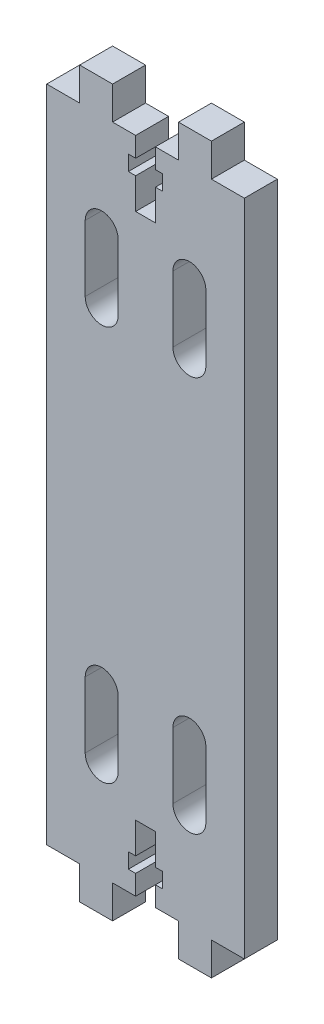
SolidWorks part; units mm, degrees
ref_plane "Front Plane" through (0, 0, 0) normal (0, 0, 1) x (1, 0, 0)
ref_plane "Top Plane" through (0, 0, 0) normal (0, 1, 0) x (1, 0, 0)
ref_plane "Right Plane" through (0, 0, 0) normal (1, 0, 0) x (0, 0, -1)
sketch "Sketch1" plane through (0, 0, 0) normal (0, 0, 1) x (1, 0, 0)
  line L0 (0, 72.0719) -> (0, -22.2682) construction
  line L1 (-15, 50) -> (-15, -50)
  line L2 (15, 50) -> (15, -50)
  line L3 (0, 0) -> (45.6439, 0) construction
  line L4 (-15, 50) -> (15, 50)
  line L5 (-15, -50) -> (15, -50)
  line L6 (-6.6565, -35) -> (-6.6565, -25) construction
  line L7 (-9.1565, -35) -> (-9.1565, -25)
  line L8 (-4.1565, -35) -> (-4.1565, -25)
  line L9 (6.6565, -35) -> (6.6565, -25) construction
  line L10 (9.1565, -35) -> (9.1565, -25)
  line L11 (4.1565, -35) -> (4.1565, -25)
  line L12 (6.6565, 35) -> (6.6565, 25) construction
  line L13 (9.1565, 35) -> (9.1565, 25)
  line L14 (4.1565, 35) -> (4.1565, 25)
  line L15 (-6.6565, 35) -> (-6.6565, 25) construction
  line L16 (-9.1565, 35) -> (-9.1565, 25)
  line L17 (-4.1565, 35) -> (-4.1565, 25)
  arc A0 (-9.1565, -35) -> (-4.1565, -35) centre (-6.6565, -35) ccw
  arc A1 (-4.1565, -25) -> (-9.1565, -25) centre (-6.6565, -25) ccw
  arc A2 (9.1565, -35) -> (4.1565, -35) centre (6.6565, -35) cw
  arc A3 (4.1565, -25) -> (9.1565, -25) centre (6.6565, -25) cw
  arc A4 (9.1565, 35) -> (4.1565, 35) centre (6.6565, 35) ccw
  arc A5 (4.1565, 25) -> (9.1565, 25) centre (6.6565, 25) ccw
  arc A6 (-9.1565, 35) -> (-4.1565, 35) centre (-6.6565, 35) cw
  arc A7 (-4.1565, 25) -> (-9.1565, 25) centre (-6.6565, 25) cw
  point P11 (-6.6565, -30)
  point P16 (0, 0)
  point P17 (0, 0)
  point P18 (0, 0)
  point P19 (0, 0)
  point P22 (6.6565, -30)
  point P29 (6.6565, 30)
  point P36 (-6.6565, 30)
  line B0 (-2.6, -47) -> (-2.6, -44.7)
  line B1 (1.5, -44.7) -> (1.5, -40)
  line B2 (-1.5, -40) -> (-1.5, -44.7)
  line B3 (-2.6, -44.7) -> (-1.5, -44.7)
  line B4 (0, -50) -> (0, -38.7792) construction
  line B5 (-1.5, -50) -> (-5, -50)
  line B6 (-5, -55) -> (-10, -55)
  line B7 (-10, -55) -> (-10, -50)
  line B8 (-5, -55) -> (-5, -50)
  line B9 (1.5, -50) -> (5, -50)
  line B10 (5, -50) -> (5, -55)
  line B11 (5, -55) -> (10, -55)
  line B12 (10, -55) -> (10, -50)
  line B13 (1.5, -50) -> (1.5, -47)
  line B14 (0, -40) -> (0, -50) construction
  line B15 (-1.5, -47) -> (-1.5, -50)
  line B16 (2.6, -44.7) -> (2.6, -47)
  line B17 (-1.5, -50) -> (1.5, -50) construction
  line B18 (1.5, -44.7) -> (2.6, -44.7)
  line B19 (2.6, -47) -> (1.5, -47)
  line B20 (1.5, -40) -> (-1.5, -40)
  line B21 (-1.5, -47) -> (-2.6, -47)
  line B22 (2.6, 47) -> (2.6, 44.7)
  line B23 (-1.5, 44.7) -> (-1.5, 40)
  line B24 (1.5, 40) -> (1.5, 44.7)
  line B25 (2.6, 44.7) -> (1.5, 44.7)
  line B26 (0, 50) -> (0, 38.7792) construction
  line B27 (1.5, 50) -> (5, 50)
  line B28 (5, 55) -> (10, 55)
  line B29 (10, 55) -> (10, 50)
  line B30 (5, 55) -> (5, 50)
  line B31 (-1.5, 50) -> (-5, 50)
  line B32 (-5, 50) -> (-5, 55)
  line B33 (-5, 55) -> (-10, 55)
  line B34 (-10, 55) -> (-10, 50)
  line B35 (-1.5, 50) -> (-1.5, 47)
  line B36 (0, 40) -> (0, 50) construction
  line B37 (1.5, 47) -> (1.5, 50)
  line B38 (-2.6, 44.7) -> (-2.6, 47)
  line B39 (1.5, 50) -> (-1.5, 50) construction
  line B40 (-1.5, 44.7) -> (-2.6, 44.7)
  line B41 (-2.6, 47) -> (-1.5, 47)
  line B42 (-1.5, 40) -> (1.5, 40)
  line B43 (1.5, 47) -> (2.6, 47)
sketch_block_instance "Insert M3 plots ep 5mm-1"
sketch_block "Insert M3 plots ep 5mm"
sketch_block_instance "Decoupe Insert M3-4"
sketch_block "Decoupe Insert M3" parameters "D1"=5.2, "D2"=3, "D3"=2.3, "D4"=3, "D5"=10
sketch_block_instance "Insert M3 plots ep 5mm-2" parameters "D1"=78.6892, "D2"=10.3216, "D3"=20, "D4"=10.3216, "D5"=18.003
extrude "Boss-Extrude1" add sketch "Sketch1" along normal blind 5 contours B28 B30 L4 B29 | B37 B43 B22 B25 B24 B42 B23 B40 B38 B41 B35 L4 L1 L5 B15 B21 B0 B3 B2 B20 B1 B18 B16 B19 B13 L2 | B33 B34 L4 B32 | B6 B8 L5 B7 | B11 B12 L5 B10
